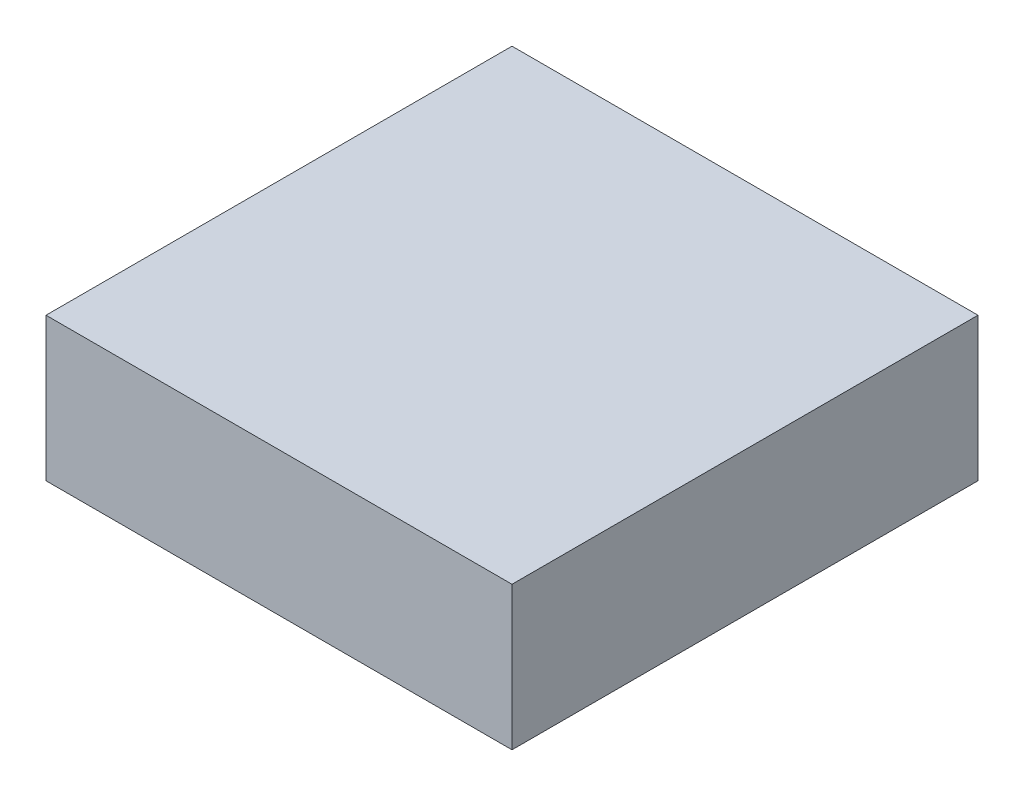
SolidWorks part; units mm, degrees
material "1060 合金"
ref_plane "前视基准面" through (0, 0, 0) normal (0, 0, 1) x (1, 0, 0)
ref_plane "上视基准面" through (0, 0, 0) normal (0, 1, 0) x (1, 0, 0)
ref_plane "右视基准面" through (0, 0, 0) normal (1, 0, 0) x (0, 0, -1)
other "Configuration Table"
sketch "草图1" plane through (0, 0, 0) normal (0, 1, 0) x (1, 0, 0)
  line L1 (-65, -65) -> (65, -65)
  line L2 (-65, -65) -> (-65, 65)
  line L3 (-65, 65) -> (65, 65)
  line L4 (65, -65) -> (65, 65)
  line L5 (-65, -65) -> (65, 65) construction
  line L6 (-65, 65) -> (65, -65) construction
  point P0 (0, 0)
  dimension "D1" = 130
  dimension "D2" = 130
extrude "凸台-拉伸1" add sketch "草图1" along normal blind 40
